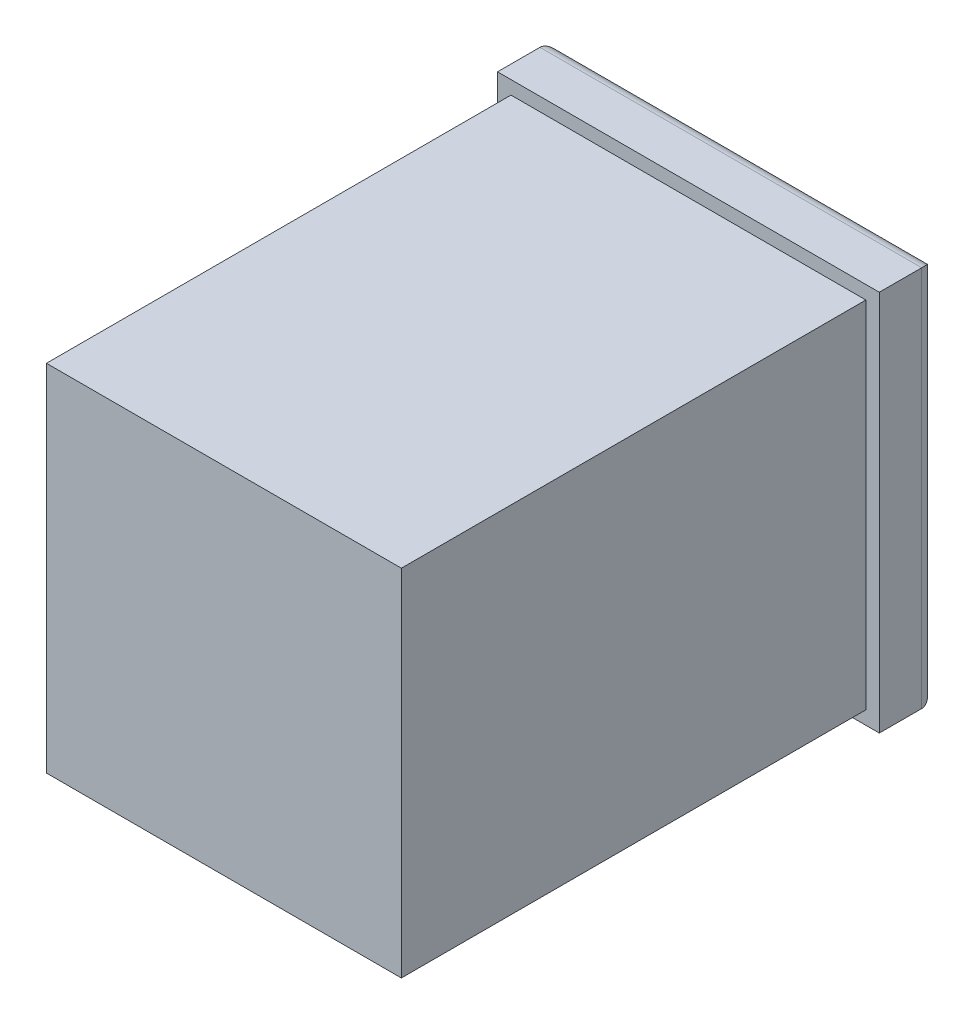
SolidWorks part; units mm, degrees
ref_plane "Front Plane" through (0, 0, 0) normal (0, 0, 1) x (1, 0, 0)
ref_plane "Top Plane" through (0, 0, 0) normal (0, 1, 0) x (1, 0, 0)
ref_plane "Right Plane" through (0, 0, 0) normal (1, 0, 0) x (0, 0, -1)
sketch "Sketch1" plane through (0, 0, 0) normal (0, 0, 1) x (1, 0, 0)
  line L1 (-12.55, -12.55) -> (12.55, -12.55)
  line L2 (-12.55, -12.55) -> (-12.55, 12.55)
  line L3 (-12.55, 12.55) -> (12.55, 12.55)
  line L4 (12.55, -12.55) -> (12.55, 12.55)
  line L5 (-12.55, -12.55) -> (12.55, 12.55) construction
  line L6 (-12.55, 12.55) -> (12.55, -12.55) construction
  point P0 (0, 0)
extrude "Boss-Extrude1" add sketch "Sketch1" along normal blind 32.85
sketch "Sketch2" plane through (0, 0, 0) normal (0, 0, -1) x (-1, 0, 0)
  line L1 (-13.5, -13.5) -> (13.5, -13.5)
  line L2 (-13.5, -13.5) -> (-13.5, 13.5)
  line L3 (-13.5, 13.5) -> (13.5, 13.5)
  line L4 (13.5, -13.5) -> (13.5, 13.5)
  line L5 (-13.5, -13.5) -> (13.5, 13.5) construction
  line L6 (-13.5, 13.5) -> (13.5, -13.5) construction
  point P0 (0, 0)
extrude "Boss-Extrude2" add sketch "Sketch2" along normal blind 4
fillet "Fillet1" radius 1 4 edges at (0, -13.5, -4) (-13.5, 0, -4) (13.5, 0, -4) (0, 13.5, -4)
sketch "Sketch3" plane through (0, 0, -4) normal (0, 0, -1) x (-1, 0, 0)
  line L0 (0, 12.5) -> (0, 9.5) construction
  line L1 (12.5, 12.5) -> (-12.5, 12.5) construction
  line L2 (0, 9.5) -> (-7.5, 9.5) construction
  line L3 (0, 9.5) -> (7.5, 9.5) construction
  line L4 (-7.5, 9.5) -> (-6.1903, 9.5)
  line L5 (-7.5, 9.5) -> (-7.5, 1.9566)
  line L6 (-7.5, 1.9566) -> (-6.1903, 1.9566)
  line L7 (-6.1903, 9.5) -> (-6.1903, 1.9566)
  line L9 (7.5, 9.5) -> (6.4762, 9.5)
  line L10 (7.5, 9.5) -> (7.5, 2.3136)
  line L11 (7.5, 2.3136) -> (6.4762, 2.3136)
  line L12 (6.4762, 9.5) -> (6.4762, 2.3136)
  circle A0 centre (0, -5.371) radius 1.4158
extrude "Cut-Extrude1" cut sketch "Sketch3" against normal blind 24
